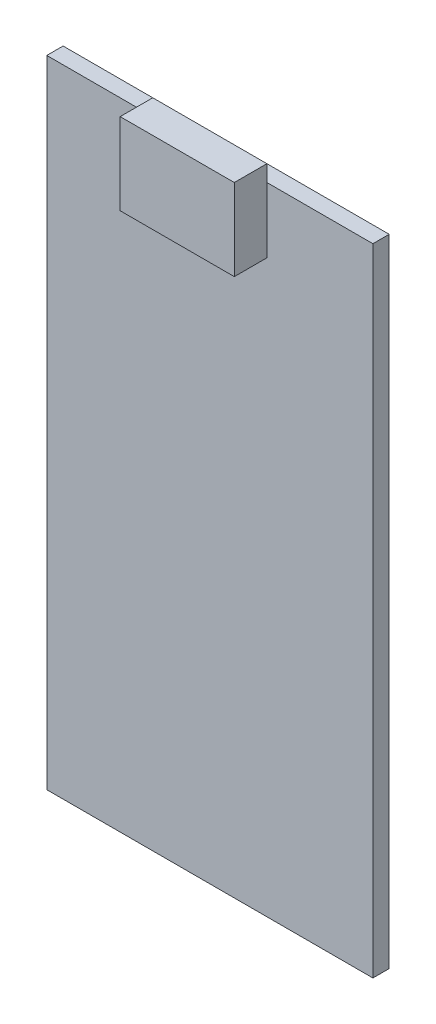
SolidWorks part; units mm, degrees
ref_plane "正面" through (0, 0, 0) normal (0, 0, 1) x (1, 0, 0)
ref_plane "平面" through (0, 0, 0) normal (0, 1, 0) x (1, 0, 0)
ref_plane "右側面" through (0, 0, 0) normal (1, 0, 0) x (0, 0, -1)
sketch "ｽｹｯﾁ1" plane through (0, 0, 0) normal (0, 0, 1) x (1, 0, 0)
  line L1 (10, -19.5) -> (-10, -19.5)
  line L2 (10, -19.5) -> (10, 19.5)
  line L3 (10, 19.5) -> (-10, 19.5)
  line L4 (-10, -19.5) -> (-10, 19.5)
  line L5 (10, -19.5) -> (-10, 19.5) construction
  line L6 (10, 19.5) -> (-10, -19.5) construction
  point P0 (0, 0)
  dimension "D1" = 39
  dimension "D2" = 20
extrude "ﾎﾞｽ - 押し出し1" add sketch "ｽｹｯﾁ1" along normal blind 1
sketch "ｽｹｯﾁ2" plane through (0, 0, 1) normal (0, 0, 1) x (1, 0, 0)
  line L0 (10, 19.5) -> (-10, 19.5) construction
  line L1 (3.5, 15.5) -> (-3.5, 15.5)
  line L2 (3.5, 15.5) -> (3.5, 20.5)
  line L3 (3.5, 20.5) -> (-3.5, 20.5)
  line L4 (-3.5, 15.5) -> (-3.5, 20.5)
  line L5 (3.5, 15.5) -> (-3.5, 20.5) construction
  line L6 (3.5, 20.5) -> (-3.5, 15.5) construction
  point P0 (0, 18)
  point P7 (0, 0)
  dimension "D1" = 1
  dimension "D2" = 5
  dimension "D3" = 7
extrude "ﾎﾞｽ - 押し出し2" add sketch "ｽｹｯﾁ2" along normal blind 2
